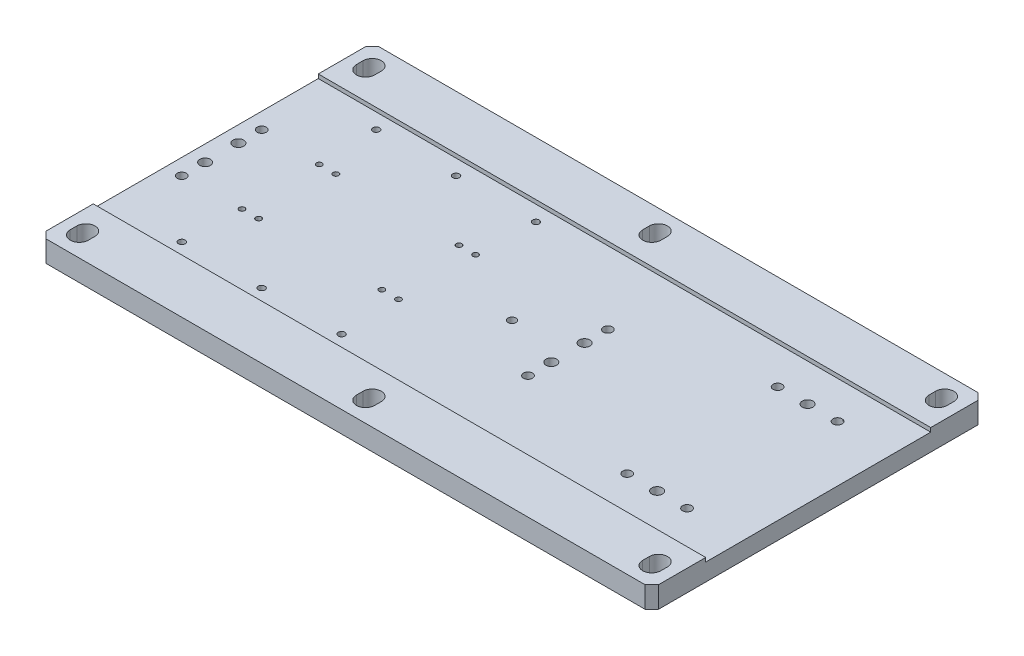
SolidWorks part; units mm, degrees
ref_plane "Front Plane" through (0, 0, 0) normal (0, 0, 1) x (1, 0, 0)
ref_plane "Top Plane" through (0, 0, 0) normal (0, 1, 0) x (1, 0, 0)
ref_plane "Right Plane" through (0, 0, 0) normal (1, 0, 0) x (0, 0, -1)
sketch "Sketch1" plane through (0, 0, 0) normal (0, 1, 0) x (1, 0, 0)
  line L1 (-230, 125) -> (230, 125)
  line L2 (-230, 125) -> (-230, -125)
  line L3 (-230, -125) -> (230, -125)
  line L4 (230, 125) -> (230, -125)
  line L5 (-230, 125) -> (230, -125) construction
  line L6 (-230, -125) -> (230, 125) construction
  point P0 (0, 0)
  dimension "D1" = 250
  dimension "D2" = 460
extrude "Boss-Extrude1" add sketch "Sketch1" along normal blind 16
sketch "Sketch2" plane through (0, 16, 0) normal (0, 1, 0) x (1, 0, 0)
  line L0 (-230, 84.5) -> (230, 84.5)
  line L1 (-230, 125) -> (-230, -125) construction
  line L2 (230, -125) -> (230, 125) construction
  line L3 (-230, -84.5) -> (230, -84.5)
  line L4 (230, -84.5) -> (230, 84.5)
  line L5 (-230, 84.5) -> (-230, -84.5)
  dimension "D1" = 84.5
  dimension "D2" = 169
extrude "Cut-Extrude1" cut sketch "Sketch2" against normal blind 3
hole_wizard "Ø6.0 (6) Diameter Hole1" positions "Sketch3" profile "Sketch4" hole size "Ø6.0" standard "ISO" end condition through all
sketch "Sketch3" plane through (0, 13, 0) normal (0, 1, 0) x (1, 0, 0)
  point P0 (0, 0)
sketch "Sketch4" plane through (0, 13, 0) normal (1, 0, 0) x (0, 0, 1)
  line L0 (0, 0) -> (0, 13)
  line L1 (0, 13) -> (3, 13)
  line L2 (3, 13) -> (3, 0)
  line L5 (3, 0) -> (0, 0)
  line L11 (0, -6.35) -> (0, 107.95) construction
  dimension "Thru Hole Dia." = 6
  dimension "Thru Hole Depth" = 13
hole_wizard "Ø8.0mm Dowel Hole1" positions "Sketch5" profile "Sketch6" hole size "Ø8.0" standard "ISO" end condition through all
sketch "Sketch5" plane through (0, 13, 0) normal (0, 1, 0) x (1, 0, 0)
  point P0 (42, 12.5)
  point P2 (42, -12.5)
  point P4 (165.5, 56.5)
  point P6 (165.5, -56.5)
  point P8 (-218, 12.5)
  point P10 (-218, -12.5)
  dimension "D1" = 12.5
  dimension "D2" = 12.5
  dimension "D3" = 56.5
  dimension "D4" = 56.5
  dimension "D5" = 42
  dimension "D6" = 165.5
  dimension "D7" = 218
sketch "Sketch6" plane through (42, 13, -12.5) normal (1, 0, 0) x (0, 0, 1)
  line L0 (0, 0) -> (0, 13)
  line L1 (0, 13) -> (4, 13)
  line L2 (4, 13) -> (4, 0)
  line L5 (4, 0) -> (0, 0)
  line L11 (0, -6.35) -> (0, 107.95) construction
  dimension "Thru Hole Dia." = 8
  dimension "Thru Hole Depth" = 13
hole_wizard "M8 Tapped Hole1" positions "Sketch7" profile "Sketch8" tap size "M8" standard "ISO" end condition through all
sketch "Sketch7" plane through (0, 13, 0) normal (0, 1, 0) x (1, 0, 0)
  point P0 (42, 30)
  point P2 (42, -30)
  point P4 (143, 56.5)
  point P6 (188, 56.5)
  point P8 (188, -56.5)
  point P10 (143, -56.5)
  point P12 (-218, 30)
  point P14 (-218, -30)
  dimension "D1" = 42
  dimension "D2" = 143
  dimension "D3" = 188
  dimension "D4" = 56.5
  dimension "D5" = 30
  dimension "D6" = 30
  dimension "D7" = 56.5
  dimension "D8" = 218
sketch "Sketch8" plane through (42, 13, -30) normal (1, 0, 0) x (0, 0, 1)
  line L0 (0, 0) -> (0, 13)
  line L1 (0, 13) -> (3.4, 13)
  line L2 (3.4, 13) -> (3.4, 0)
  line L5 (3.4, 0) -> (0, 0)
  line L11 (0, -6.35) -> (0, 107.95) construction
  dimension "Thru Tap Drill Dia." = 6.8
  dimension "Thru Tap Drill Depth" = 13
cosmetic thread "Hole Thread1" parameters "D2"=8
cosmetic thread "Hole Thread2" parameters "D2"=8
cosmetic thread "Hole Thread3" parameters "D2"=8
cosmetic thread "Hole Thread4" parameters "D2"=8
cosmetic thread "Hole Thread5" parameters "D2"=8
cosmetic thread "Hole Thread6" parameters "D2"=8
cosmetic thread "Hole Thread7" parameters "D2"=8
cosmetic thread "Hole Thread8" parameters "D2"=8
hole_wizard "M6 Tapped Hole1" positions "Sketch9" profile "Sketch10" tap size "M6" standard "ISO" end condition through all
sketch "Sketch9" plane through (0, 13, 0) normal (0, 1, 0) x (1, 0, 0)
  point P0 (-175, 73)
  point P2 (-115, 73)
  point P4 (-55, 73)
  point P6 (-175, -73)
  point P8 (-115, -73)
  point P10 (-55, -73)
  dimension "D1" = 73
  dimension "D2" = 175
  dimension "D3" = 115
  dimension "D4" = 55
  dimension "D5" = 73
sketch "Sketch10" plane through (-175, 13, -73) normal (1, 0, 0) x (0, 0, 1)
  line L0 (0, 0) -> (0, 13)
  line L1 (0, 13) -> (2.5, 13)
  line L2 (2.5, 13) -> (2.5, 0)
  line L5 (2.5, 0) -> (0, 0)
  line L11 (0, -6.35) -> (0, 107.95) construction
  dimension "Thru Tap Drill Dia." = 5
  dimension "Thru Tap Drill Depth" = 13
cosmetic thread "Hole Thread9" parameters "D2"=6
cosmetic thread "Hole Thread10" parameters "D2"=6
cosmetic thread "Hole Thread11" parameters "D2"=6
cosmetic thread "Hole Thread12" parameters "D2"=6
cosmetic thread "Hole Thread13" parameters "D2"=6
cosmetic thread "Hole Thread14" parameters "D2"=6
hole_wizard "M5 Tapped Hole1" positions "Sketch11" profile "Sketch12" tap size "M5" standard "ISO" end condition through all
sketch "Sketch11" plane through (0, 13, 0) normal (0, 1, 0) x (1, 0, 0)
  point P0 (-56.3, 29)
  point P2 (-56.3, -29)
  point P4 (-68.8, 29)
  point P6 (-68.8, -29)
  point P8 (-173.8, 29)
  point P10 (-173.8, -29)
  point P13 (-161.3, 29)
  point P15 (-161.3, -29)
  dimension "D1" = 29
  dimension "D2" = 29
  dimension "D3" = 56.3
  dimension "D4" = 68.8
  dimension "D5" = 161.3
  dimension "D6" = 173.8
sketch "Sketch12" plane through (-56.3, 13, -29) normal (1, 0, 0) x (0, 0, 1)
  line L0 (0, 0) -> (0, 13)
  line L1 (0, 13) -> (2.1, 13)
  line L2 (2.1, 13) -> (2.1, 0)
  line L5 (2.1, 0) -> (0, 0)
  line L11 (0, -6.35) -> (0, 107.95) construction
  dimension "Thru Tap Drill Dia." = 4.2
  dimension "Thru Tap Drill Depth" = 13
cosmetic thread "Hole Thread15" parameters "D2"=5
cosmetic thread "Hole Thread16" parameters "D2"=5
cosmetic thread "Hole Thread17" parameters "D2"=5
cosmetic thread "Hole Thread18" parameters "D2"=5
cosmetic thread "Hole Thread19" parameters "D2"=5
cosmetic thread "Hole Thread20" parameters "D2"=5
cosmetic thread "Hole Thread21" parameters "D2"=5
cosmetic thread "Hole Thread22" parameters "D2"=5
sketch "Sketch13" plane through (0, 16, 0) normal (0, 1, 0) x (1, 0, 0)
  line L0 (-215, 105) -> (-215, 110) construction
  line L1 (-221.8, 105) -> (-221.8, 110)
  line L2 (-208.2, 105) -> (-208.2, 110)
  line L3 (0, 105) -> (0, 110) construction
  line L4 (-6.8, 105) -> (-6.8, 110)
  line L5 (6.8, 105) -> (6.8, 110)
  line L6 (215, 105) -> (215, 110) construction
  line L7 (208.2, 105) -> (208.2, 110)
  line L8 (221.8, 105) -> (221.8, 110)
  line L9 (215, -105) -> (215, -110) construction
  line L10 (221.8, -105) -> (221.8, -110)
  line L11 (208.2, -105) -> (208.2, -110)
  line L12 (0, -105) -> (0, -110) construction
  line L13 (6.8, -105) -> (6.8, -110)
  line L14 (-6.8, -105) -> (-6.8, -110)
  line L15 (-215, -105) -> (-215, -110) construction
  line L16 (-208.2, -105) -> (-208.2, -110)
  line L17 (-221.8, -105) -> (-221.8, -110)
  arc A0 (-221.8, 105) -> (-208.2, 105) centre (-215, 105) ccw
  arc A1 (-208.2, 110) -> (-221.8, 110) centre (-215, 110) ccw
  arc A2 (-6.8, 105) -> (6.8, 105) centre (0, 105) ccw
  arc A3 (6.8, 110) -> (-6.8, 110) centre (0, 110) ccw
  arc A4 (208.2, 105) -> (221.8, 105) centre (215, 105) ccw
  arc A5 (221.8, 110) -> (208.2, 110) centre (215, 110) ccw
  arc A6 (221.8, -105) -> (208.2, -105) centre (215, -105) ccw
  arc A7 (208.2, -110) -> (221.8, -110) centre (215, -110) ccw
  arc A8 (6.8, -105) -> (-6.8, -105) centre (0, -105) ccw
  arc A9 (-6.8, -110) -> (6.8, -110) centre (0, -110) ccw
  arc A10 (-208.2, -105) -> (-221.8, -105) centre (-215, -105) ccw
  arc A11 (-221.8, -110) -> (-208.2, -110) centre (-215, -110) ccw
  point P2 (-215, 107.5)
  point P7 (0, 107.5)
  point P14 (215, 107.5)
  point P21 (215, -107.5)
  point P28 (0, -107.5)
  point P35 (-215, -107.5)
  dimension "D1" = 6.8
  dimension "D2" = 6.8
  dimension "D3" = 6.8
  dimension "D4" = 6.8
  dimension "D5" = 6.8
  dimension "D6" = 6.8
  dimension "D7" = 105
  dimension "D8" = 110
  dimension "D9" = 105
  dimension "D10" = 110
  dimension "D11" = 215
  dimension "D12" = 215
extrude "Cut-Extrude2" cut sketch "Sketch13" against normal through all
chamfer "Chamfer1" distance 5 angle 45 4 edges at (230, 8, 125) (230, 8, -125) (-230, 8, 125) (-230, 8, -125)
